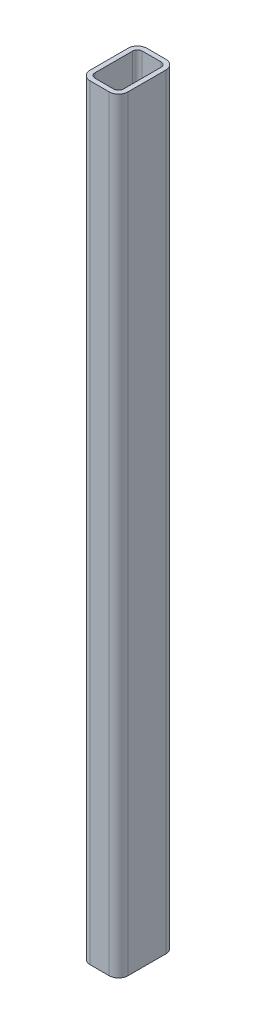
SolidWorks part; units mm, degrees
material "Fundición gris"
ref_plane "Alzado" through (0, 0, 0) normal (0, 0, 1) x (1, 0, 0)
ref_plane "Planta" through (0, 0, 0) normal (0, 1, 0) x (1, 0, 0)
ref_plane "Vista lateral" through (0, 0, 0) normal (1, 0, 0) x (0, 0, -1)
sketch "Croquis1" plane through (0, 0, 0) normal (0, 0, 1) x (1, 0, 0)
  line L0 (0, 0) -> (0, 1030)
  dimension "D1" = 1030
other "Tubo rectangular 3 X 2 X 0.25(1)"
ref_plane "Plano1" through (0, 0, 0) normal (0, 1, 0) x (-1, 0, 0)
sketch "Sketch1" plane through (0, 0, 0) normal (0, 1, 0) x (-1, 0, 0)
  line L0 (-12.7, -31.75) -> (12.7, -31.75)
  line L1 (-19.05, -25.4) -> (-19.05, 25.4)
  line L2 (12.7, 31.75) -> (-12.7, 31.75)
  line L3 (19.05, 25.4) -> (19.05, -25.4)
  line L4 (-12.7, -38.1) -> (12.7, -38.1)
  line L5 (-25.4, -25.4) -> (-25.4, 25.4)
  line L6 (12.7, 38.1) -> (-12.7, 38.1)
  line L7 (25.4, 25.4) -> (25.4, -25.4)
  line L8 (0, 0) -> (25.4, 0) construction
  line L9 (0, 0) -> (0, 38.1) construction
  arc A0 (25.4, 25.4) -> (12.7, 38.1) centre (12.7, 25.4) ccw
  arc A1 (12.7, -38.1) -> (25.4, -25.4) centre (12.7, -25.4) ccw
  arc A2 (-25.4, -25.4) -> (-12.7, -38.1) centre (-12.7, -25.4) ccw
  arc A3 (-12.7, 38.1) -> (-25.4, 25.4) centre (-12.7, 25.4) ccw
  arc A4 (-12.7, 31.75) -> (-19.05, 25.4) centre (-12.7, 25.4) ccw
  arc A5 (19.05, 25.4) -> (12.7, 31.75) centre (12.7, 25.4) ccw
  arc A6 (12.7, -31.75) -> (19.05, -25.4) centre (12.7, -25.4) ccw
  arc A7 (-19.05, -25.4) -> (-12.7, -31.75) centre (-12.7, -25.4) ccw
  point P3 (0, -38.1)
  point P4 (-25.4, 0)
  point P5 (0, 0)
  point P6 (25.4, -38.1)
  point P7 (-25.4, -38.1)
  point P8 (-25.4, 38.1)
  point P33 (0, 0)
  point P35 (25.4, 38.1)
  point P36 (25.4, 0)
  point P37 (0, 38.1)
  dimension "D1" = 12.7
  dimension "Thickness" = 6.35
  dimension "V_leg" = 76.2
  dimension "H_leg" = 50.8
